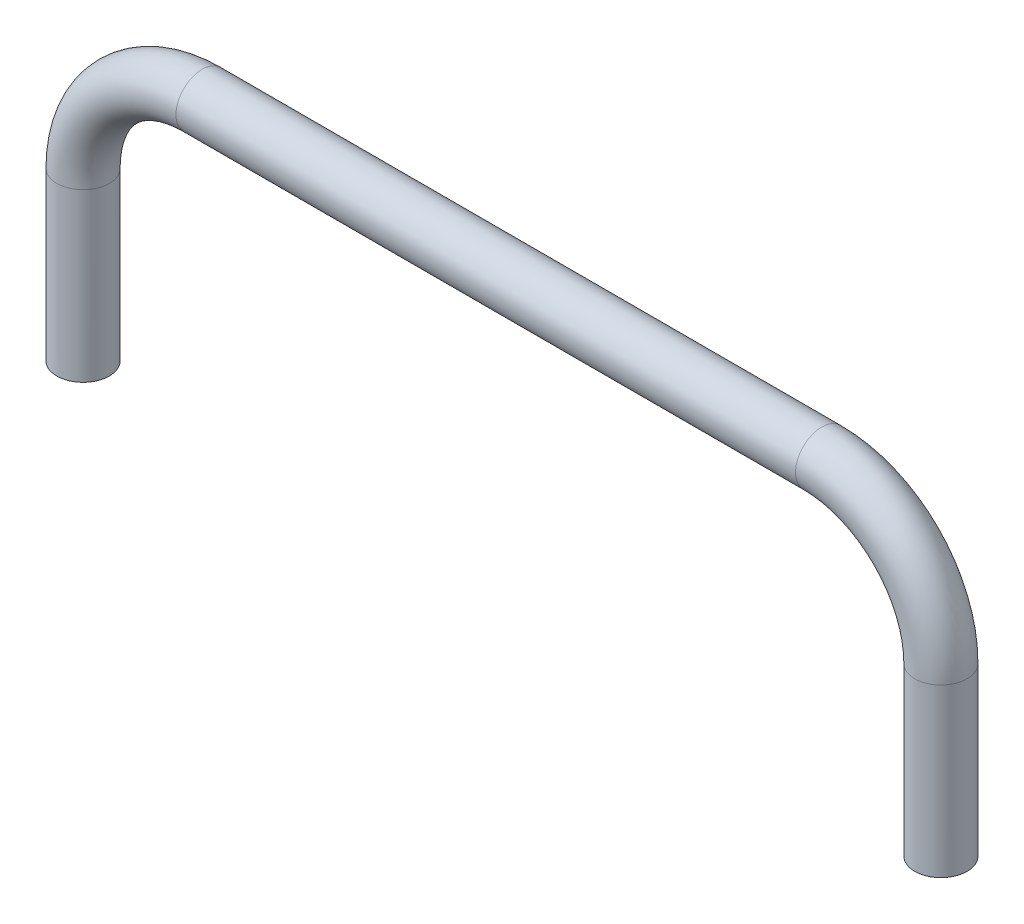
SolidWorks part; units mm, degrees
ref_plane "前视基准面" through (0, 0, 0) normal (0, 0, 1) x (1, 0, 0)
ref_plane "上视基准面" through (0, 0, 0) normal (0, 1, 0) x (1, 0, 0)
ref_plane "右视基准面" through (0, 0, 0) normal (1, 0, 0) x (0, 0, -1)
sketch "草图1" plane through (0, 0, 0) normal (0, 1, 0) x (1, 0, 0)
  circle A0 centre (-180, 0) radius 11
  dimension "D1" = 22
  dimension "D2" = 180
sketch "草图2" plane through (0, 0, 0) normal (0, 0, 1) x (1, 0, 0)
  line L0 (-180, 0) -> (-180, 70)
  line L1 (-169, 0) -> (-191, 0) construction
  line L2 (0, 164.2881) -> (0, -45.5582) construction
  line L3 (-130, 120) -> (130, 120)
  line L4 (180, 0) -> (180, 70)
  arc A0 (-180, 70) -> (-130, 120) centre (-130, 70) cw
  arc A1 (180, 70) -> (130, 120) centre (130, 70) ccw
  point P12 (0, 136.0933)
  point P16 (0, 120)
  dimension "D2" = 50
  dimension "D1" = 70
sweep "扫描1" add profiles "草图1" path "草图2"
